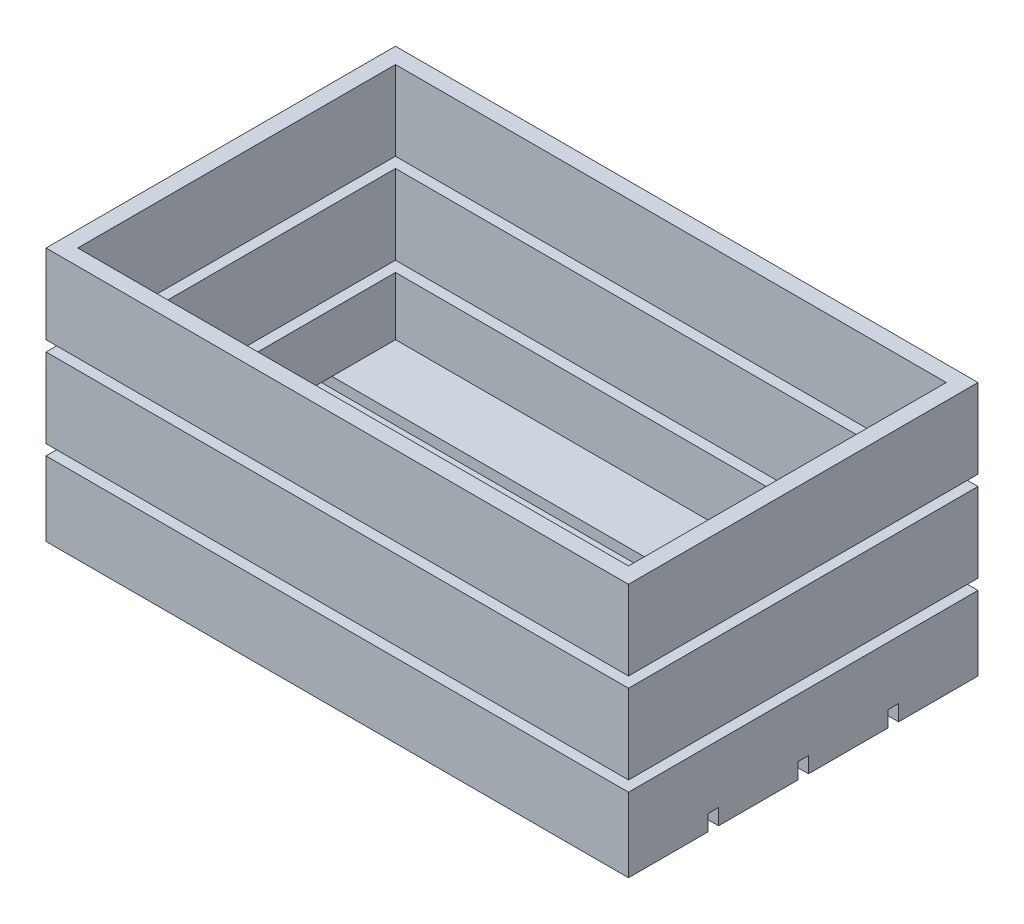
SolidWorks part; units mm, degrees
ref_plane "Front Plane" through (0, 0, 0) normal (0, 0, 1) x (1, 0, 0)
ref_plane "Top Plane" through (0, 0, 0) normal (0, 1, 0) x (1, 0, 0)
ref_plane "Right Plane" through (0, 0, 0) normal (1, 0, 0) x (0, 0, -1)
sketch "Sketch1" plane through (0, 0, 0) normal (0, 1, 0) x (1, 0, 0)
  line L1 (-349.25, 209.55) -> (349.25, 209.55)
  line L2 (-349.25, 209.55) -> (-349.25, -209.55)
  line L3 (-349.25, -209.55) -> (349.25, -209.55)
  line L4 (349.25, 209.55) -> (349.25, -209.55)
  line L5 (-349.25, 209.55) -> (349.25, -209.55) construction
  line L6 (-349.25, -209.55) -> (349.25, 209.55) construction
  point P0 (0, 0)
  dimension "D1" = 698.5
  dimension "D2" = 419.1
extrude "Boss-Extrude1" add sketch "Sketch1" along normal blind 304.8
shell "Shell1" thickness 19.05
sketch "Sketch2" plane through (0, 0, 209.55) normal (0, 0, 1) x (1, 0, 0)
  line L0 (-349.25, 304.8) -> (-349.25, 0) construction
  line L1 (-349.25, 209.55) -> (349.25, 209.55)
  line L2 (-349.25, 209.55) -> (-349.25, 196.85)
  line L3 (-349.25, 196.85) -> (349.25, 196.85)
  line L4 (349.25, 209.55) -> (349.25, 196.85)
  line L5 (349.25, 304.8) -> (349.25, 0) construction
  line L6 (-349.25, 304.8) -> (349.25, 304.8) construction
  line L7 (-349.25, 101.6) -> (349.25, 101.6)
  line L8 (-349.25, 101.6) -> (-349.25, 88.9)
  line L9 (-349.25, 88.9) -> (349.25, 88.9)
  line L10 (349.25, 101.6) -> (349.25, 88.9)
  dimension "D1" = 95.25
  dimension "D2" = 12.7
  dimension "D3" = 95.25
  dimension "D4" = 12.7
extrude "Cut-Extrude1" cut sketch "Sketch2" against normal through all
sketch "Sketch5" [suppressed] plane through (0, 0, 209.55) normal (0, 0, 1) x (1, 0, 0)
  line L0 (-304.8, 190.5) -> (-304.8, 0) construction
  line L1 (-304.8, 82.55) -> (304.8, 82.55)
  line L2 (-304.8, 82.55) -> (-304.8, 95.25)
  line L3 (-304.8, 95.25) -> (304.8, 95.25)
  line L4 (304.8, 82.55) -> (304.8, 95.25)
  line L5 (304.8, 190.5) -> (304.8, 0) construction
  line L6 (-304.8, 190.5) -> (304.8, 190.5) construction
  dimension "D1" = 95.25
  dimension "D2" = 12.7
extrude "Cut-Extrude2" [suppressed] cut sketch "Sketch5" against normal through all
sketch "Sketch6" plane through (0, 0, 0) normal (0, -1, 0) x (1, 0, 0)
  line L0 (-349.25, -209.55) -> (-349.25, 209.55) construction
  line L1 (-349.25, 114.3) -> (349.25, 114.3)
  line L2 (-349.25, 114.3) -> (-349.25, 101.6)
  line L3 (-349.25, 101.6) -> (349.25, 101.6)
  line L4 (349.25, 114.3) -> (349.25, 101.6)
  line L5 (349.25, 209.55) -> (349.25, -209.55) construction
  line L6 (-349.25, 209.55) -> (349.25, 209.55) construction
  line L7 (-349.25, 6.35) -> (349.25, 6.35)
  line L8 (-349.25, 6.35) -> (-349.25, -6.35)
  line L9 (-349.25, -6.35) -> (349.25, -6.35)
  line L10 (349.25, 6.35) -> (349.25, -6.35)
  line L11 (-349.25, -101.6) -> (349.25, -101.6)
  line L12 (-349.25, -101.6) -> (-349.25, -114.3)
  line L13 (-349.25, -114.3) -> (349.25, -114.3)
  line L14 (349.25, -101.6) -> (349.25, -114.3)
  line L15 (349.25, -209.55) -> (-349.25, -209.55) construction
  dimension "D1" = 95.25
  dimension "D2" = 12.7
  dimension "D3" = 95.25
  dimension "D4" = 12.7
  dimension "D5" = 95.25
  dimension "D6" = 12.7
  dimension "D7" = 95.25
extrude "Cut-Extrude3" cut sketch "Sketch6" against normal blind 19.05
sketch "Sketch7" [suppressed] plane through (0, 0, 0) normal (0, -1, 0) x (1, 0, 0)
  line L0 (-304.8, -209.55) -> (-304.8, 209.55) construction
  line L1 (-304.8, 114.3) -> (304.8, 114.3)
  line L2 (-304.8, 114.3) -> (-304.8, 101.6)
  line L3 (-304.8, 101.6) -> (304.8, 101.6)
  line L4 (304.8, 114.3) -> (304.8, 101.6)
  line L5 (304.8, 209.55) -> (304.8, -209.55) construction
  line L6 (-304.8, 209.55) -> (304.8, 209.55) construction
  line L7 (-304.8, 6.35) -> (304.8, 6.35)
  line L8 (-304.8, 6.35) -> (-304.8, -6.35)
  line L9 (-304.8, -6.35) -> (304.8, -6.35)
  line L10 (304.8, 6.35) -> (304.8, -6.35)
  line L11 (-304.8, -101.6) -> (304.8, -101.6)
  line L12 (-304.8, -101.6) -> (-304.8, -114.3)
  line L13 (-304.8, -114.3) -> (304.8, -114.3)
  line L14 (304.8, -101.6) -> (304.8, -114.3)
  dimension "D1" = 95.25
  dimension "D2" = 12.7
  dimension "D3" = 95.25
  dimension "D4" = 12.7
  dimension "D5" = 95.25
  dimension "D6" = 12.7
extrude "Cut-Extrude4" [suppressed] cut sketch "Sketch7" against normal blind 19.05
equation "\"D6@Sketch6\"=\"D2@Sketch6\""
equation "\"D4@Sketch6\"=\"D2@Sketch6\""
equation "\"D3@Sketch6\"=\"D1@Sketch6\""
equation "\"D5@Sketch6\"=\"D3@Sketch6\""
equation "\"D3@Sketch7\"=\"D1@Sketch7\""
equation "\"D4@Sketch7\"=\"D2@Sketch7\""
equation "\"D5@Sketch7\"=\"D1@Sketch7\""
equation "\"D6@Sketch7\"=\"D2@Sketch7\""
